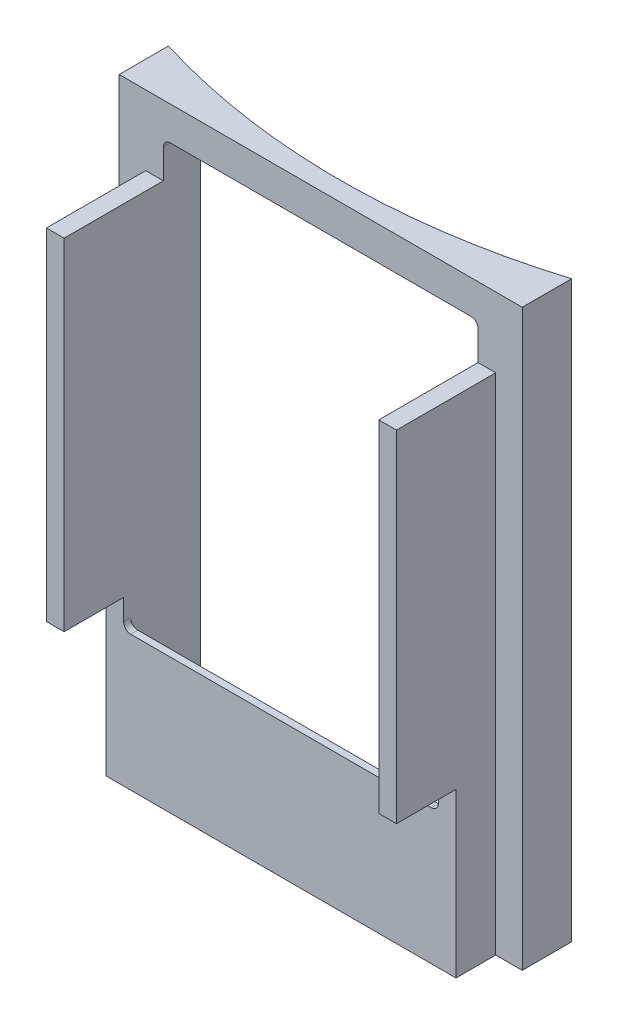
SolidWorks part; units mm, degrees
ref_plane "Front Plane" through (0, 0, 0) normal (0, 0, 1) x (1, 0, 0)
ref_plane "Top Plane" through (0, 0, 0) normal (0, 1, 0) x (1, 0, 0)
ref_plane "Right Plane" through (0, 0, 0) normal (1, 0, 0) x (0, 0, -1)
sketch "Sketch1" plane through (0, 0, 0) normal (0, 0, 1) x (1, 0, 0)
  line L1 (-46.99, 86.36) -> (97.79, 86.36)
  line L2 (-46.99, 86.36) -> (-46.99, -119.888)
  line L3 (-46.99, -119.888) -> (97.79, -119.888)
  line L4 (97.79, 86.36) -> (97.79, -119.888)
  dimension "D1" = 144.78
  dimension "D2" = 206.248
extrude "Extrude1" add sketch "Sketch1" along normal blind 252.4252
sketch "Sketch2" plane through (0, 86.36, 0) normal (0, 1, 0) x (-1, 0, 0)
  line L0 (-97.79, 0) -> (46.99, 0) construction
  circle A1 centre (-25.4, 0) radius 245.618
sketch "Sketch7" plane through (0, 0, 252.4252) normal (0, 0, 1) x (1, 0, 0)
  line L0 (-46.99, 86.36) -> (-46.99, -119.888) construction
  line L1 (-37.465, 76.835) -> (88.265, 76.835)
  line L2 (-37.465, 76.835) -> (-37.465, -119.888)
  line L3 (-37.465, -119.888) -> (88.265, -119.888)
  line L4 (88.265, 76.835) -> (88.265, -119.888)
  line L5 (97.79, -119.888) -> (97.79, 86.36) construction
  line L6 (97.79, 86.36) -> (-46.99, 86.36) construction
  line L7 (-46.99, -119.888) -> (97.79, -119.888) construction
  point P8 (25.4, 76.835)
  point P9 (0, 0)
  dimension "D1" = 9.525
  dimension "D2" = 9.525
  dimension "D3" = 9.525
extrude "Extrude5" add sketch "Sketch7" along normal blind 35.6442
sketch "Sketch4" plane through (0, 0, 252.4252) normal (0, 0, 1) x (1, 0, 0)
  line L0 (97.79, 86.36) -> (-46.99, 86.36) construction
  line L1 (-31.115, 71.374) -> (81.915, 71.374)
  line L2 (-31.115, 71.374) -> (-31.115, -71.374)
  line L3 (-31.115, -71.374) -> (81.915, -71.374)
  line L4 (81.915, 71.374) -> (81.915, -71.374)
  line L5 (88.265, 76.835) -> (-37.465, 76.835) construction
  line L6 (88.265, 76.835) -> (-37.465, 76.835) construction
  point P4 (25.4, 71.374)
  point P5 (25.4, 86.36)
  point P6 (25.4, 76.835)
  dimension "D1" = 5.461
  dimension "D2" = 142.748
extrude "Extrude2" cut sketch "Sketch4" against normal blind 273.8502 and the other way blind 42.08
sketch "Sketch10" plane through (0, 0, 0) normal (0, 0, -1) x (-1, 0, 0)
  line L0 (46.99, -119.888) -> (-97.79, -119.888) construction
  line L1 (-81.915, 71.374) -> (31.115, 71.374)
  line L2 (-81.915, 71.374) -> (-81.915, 74.295)
  line L3 (-81.915, 74.295) -> (31.115, 74.295)
  line L4 (31.115, 71.374) -> (31.115, 74.295)
  line L5 (-81.915, -71.374) -> (31.115, -71.374)
  line L6 (-81.915, -71.374) -> (-81.915, -117.348)
  line L7 (-81.915, -117.348) -> (31.115, -117.348)
  line L8 (31.115, -71.374) -> (31.115, -117.348)
  dimension "D1" = 2.54
extrude "Extrude8" cut sketch "Sketch10" against normal blind 264.16
sketch "Sketch11" plane through (0, 0, 264.16) normal (0, 0, -1) x (-1, 0, 0)
  line L0 (-81.915, 71.374) -> (31.115, 71.374) construction
  line L1 (31.115, 74.295) -> (-81.915, 74.295)
  line L2 (31.115, 74.295) -> (31.115, 71.374)
  line L3 (31.115, 71.374) -> (-81.915, 71.374)
  line L4 (-81.915, 74.295) -> (-81.915, 71.374)
extrude "Extrude9" cut sketch "Sketch11" against normal blind 21.59
fillet "Fillet1" radius 2.54 8 edges at (81.915, -71.374, 276.1147) (-31.115, -71.374, 276.1147) (81.915, 71.374, 286.9097) (-31.115, 71.374, 286.9097) (81.915, -117.348, 132.08) (-31.115, -117.348, 132.08) (-31.115, 74.295, 142.875) (81.915, 74.295, 142.875)
extrude "Extrude4" cut sketch "Sketch2" against normal blind 230
sketch "Sketch12" plane through (0, 0, 288.0694) normal (0, 0, 1) x (1, 0, 0)
  line L0 (88.265, -119.888) -> (88.265, 76.835) construction
  line L1 (-37.465, -119.888) -> (88.265, -119.888)
  line L2 (-37.465, -119.888) -> (-37.465, -76.835)
  line L3 (-37.465, -76.835) -> (88.265, -76.835)
  line L4 (88.265, -119.888) -> (88.265, -76.835)
  dimension "D1" = 5.461
extrude "Extrude10" cut sketch "Sketch12" against normal blind 21.3694
sketch "Sketch14" plane through (0, 76.835, 0) normal (0, 1, 0) x (1, 0, 0)
  line L1 (-44.4777, -292.1573) -> (88.265, -292.1573)
  line L2 (-44.4777, -292.1573) -> (-44.4777, -252.4252)
  line L3 (-44.4777, -252.4252) -> (88.265, -252.4252)
  line L4 (88.265, -292.1573) -> (88.265, -252.4252)
  line L5 (-44.4777, -292.1573) -> (88.265, -252.4252) construction
  line L6 (-44.4777, -252.4252) -> (88.265, -292.1573) construction
  point P0 (21.8937, -272.2912)
extrude "Cut-Extrude1" cut sketch "Sketch14" against normal blind 15.624
sketch "Sketch15" plane through (0, -76.835, 0) normal (0, -1, 0) x (1, 0, 0)
  line L1 (-46.3219, 289.9792) -> (98.0258, 289.9792)
  line L2 (-46.3219, 289.9792) -> (-46.3219, 266.7)
  line L3 (-46.3219, 266.7) -> (98.0258, 266.7)
  line L4 (98.0258, 289.9792) -> (98.0258, 266.7)
  line L5 (-46.3219, 289.9792) -> (98.0258, 266.7) construction
  line L6 (-46.3219, 266.7) -> (98.0258, 289.9792) construction
  point P0 (25.8519, 278.3396)
extrude "Cut-Extrude2" cut sketch "Sketch15" against normal blind 15.624
equation "\"extrusion_amount\" = 0.31in + 5.14mm + 2.61mm"
equation "\"D1@Cut-Extrude2\"=\"extrusion_amount\""
equation "\"D1@Cut-Extrude1\"=\"extrusion_amount\""
